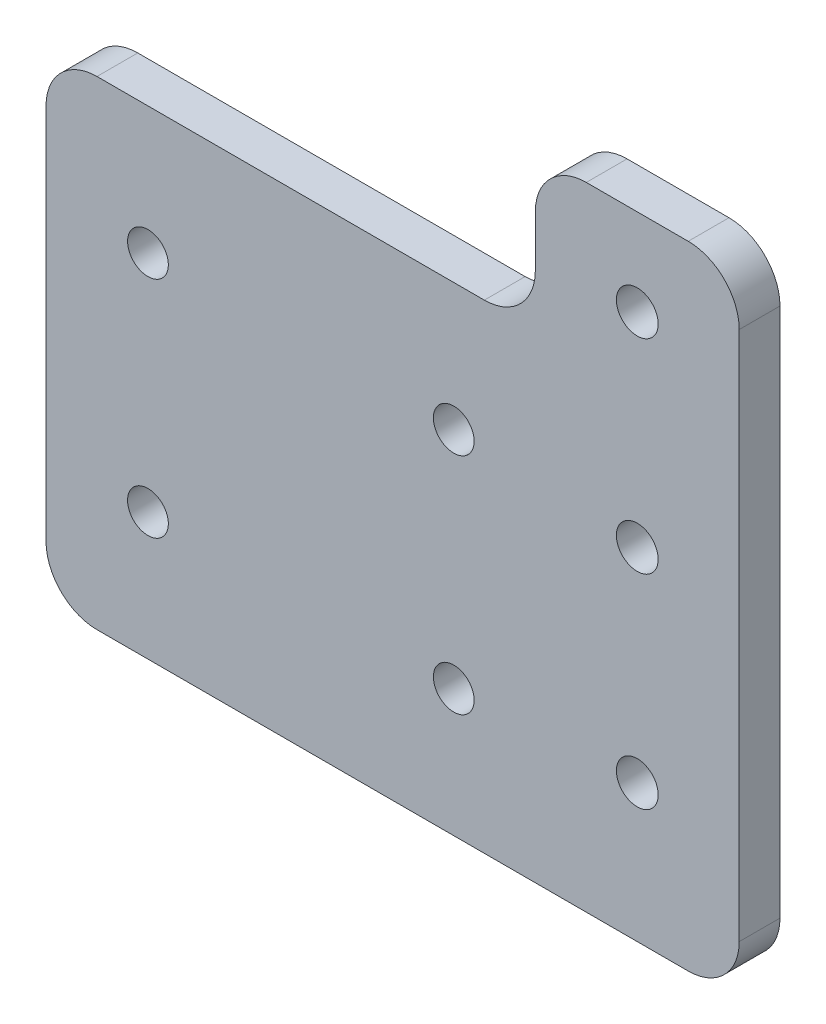
SolidWorks part; units mm, degrees
material "A-玻璃纤维"
ref_plane "前视基准面" through (0, 0, 0) normal (0, 0, 1) x (1, 0, 0)
ref_plane "上视基准面" through (0, 0, 0) normal (0, 1, 0) x (1, 0, 0)
ref_plane "右视基准面" through (0, 0, 0) normal (1, 0, 0) x (0, 0, -1)
other "Configuration Table"
sketch "草图1" plane through (0, 0, 0) normal (0, 0, 1) x (1, 0, 0)
  line L1 (0, 0) -> (68, 0)
  line L2 (0, 0) -> (0, 47)
  line L3 (0, 47) -> (68, 47)
  line L4 (68, 0) -> (68, 47)
  dimension "D1" = 68
  dimension "D2" = 47
extrude "凸台-拉伸1" add sketch "草图1" along normal blind 4
fillet "圆角1" [suppressed] radius 10
sketch "草图2" plane through (0, 0, 4) normal (0, 0, 1) x (1, 0, 0)
  line L0 (0, 47) -> (0, 0) construction
  line L1 (0, 23.5) -> (85.3311, 23.5) construction
  line L2 (30, 23.5) -> (115.3311, 23.5) construction
  line L3 (68, 0) -> (68, 47) construction
  circle A0 centre (10, 34.5) radius 2
  circle A1 centre (10, 12.5) radius 2
  circle A2 centre (40, 34.5) radius 2
  circle A3 centre (40, 12.5) radius 2
  circle A4 centre (58, 33.5) radius 2.05
  circle A5 centre (58, 13.5) radius 2.05
  dimension "D1" = 4
  dimension "D3" = 22
  dimension "D5" = 30
  dimension "D6" = 4.1
  dimension "D7" = 20
  dimension "D8" = 10
  dimension "D2" = 10
  dimension "D4" = 2
extrude "切除-拉伸1" cut sketch "草图2" against normal blind 4
sketch "草图5" plane through (0, 0, 4) normal (0, 0, 1) x (1, 0, 0)
  line L1 (68, 47) -> (48, 47)
  line L2 (68, 47) -> (68, 62)
  line L3 (68, 62) -> (48, 62)
  line L4 (48, 47) -> (48, 62)
  dimension "D1" = 15
  dimension "D2" = 20
extrude "凸台-拉伸3" add sketch "草图5" against normal blind 4
sketch "草图6" plane through (0, 0, 4) normal (0, 0, 1) x (1, 0, 0)
  circle A0 centre (58, 33.5) radius 2.05 construction
  circle A1 centre (58, 33.5) radius 2.05
  circle A2 centre (58, 53.5) radius 2.05
  dimension "D1" = 2
extrude "切除-拉伸3" cut sketch "草图6" against normal blind 12
fillet "圆角3" radius 5 6 edges at (0, 0, 2) (68, 0, 2) (48, 62, 2) (48, 47, 2) (0, 47, 2) (68, 62, 2)
